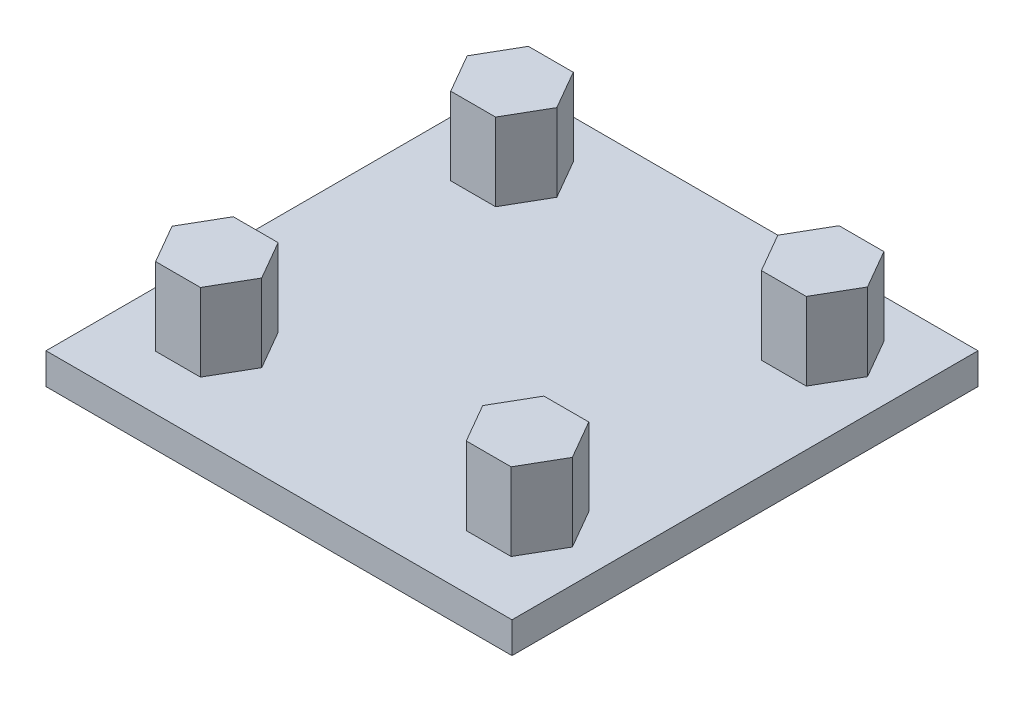
SolidWorks part; units mm, degrees
ref_plane "Front" through (0, 0, 0) normal (0, 0, 1) x (1, 0, 0)
ref_plane "Top" through (0, 0, 0) normal (0, 1, 0) x (1, 0, 0)
ref_plane "Right" through (0, 0, 0) normal (1, 0, 0) x (0, 0, -1)
sketch "Sketch1" plane through (0, 0, 0) normal (0, 1, 0) x (1, 0, 0)
  line L1 (-38.1, 38.1) -> (38.1, 38.1)
  line L2 (-38.1, 38.1) -> (-38.1, -38.1)
  line L3 (-38.1, -38.1) -> (38.1, -38.1)
  line L4 (38.1, 38.1) -> (38.1, -38.1)
  line L5 (-38.1, 38.1) -> (38.1, -38.1) construction
  line L6 (-38.1, -38.1) -> (38.1, 38.1) construction
  point P0 (0, 0)
  dimension "D1" = 76.2
extrude "Boss-Extrude1" add sketch "Sketch1" along normal blind 5.08
sketch "Sketch2" plane through (0, 5.08, 0) normal (0, 1, 0) x (1, 0, 0)
  line L3 (-2.794, 0) -> (2.794, 0) construction
  line L4 (-21.7338, 19.05) -> (-18.0677, 25.4)
  line L5 (-18.0677, 25.4) -> (-21.7338, 31.75)
  line L6 (-21.7338, 31.75) -> (-29.0662, 31.75)
  line L7 (-29.0662, 31.75) -> (-32.7323, 25.4)
  line L8 (-32.7323, 25.4) -> (-29.0662, 19.05)
  line L9 (-29.0662, 19.05) -> (-21.7338, 19.05)
  line L12 (38.1, 38.1) -> (-38.1, 38.1) construction
  line L13 (-38.1, 38.1) -> (-38.1, -38.1) construction
  circle A1 centre (-25.4, 25.4) radius 6.35 construction
  point P3 (-19.0547, 17.2427)
  dimension "D1" = 6.35
  dimension "D2" = 12.7
  dimension "D3" = 12.7
extrude "Boss-Extrude2" add sketch "Sketch2" along normal blind 12.7
pattern_linear "LPattern1" count 2 spacing 50.8 along (1, 0, 0) count 2 spacing 48.26 along (0, 0, 1) of "Boss-Extrude2"
